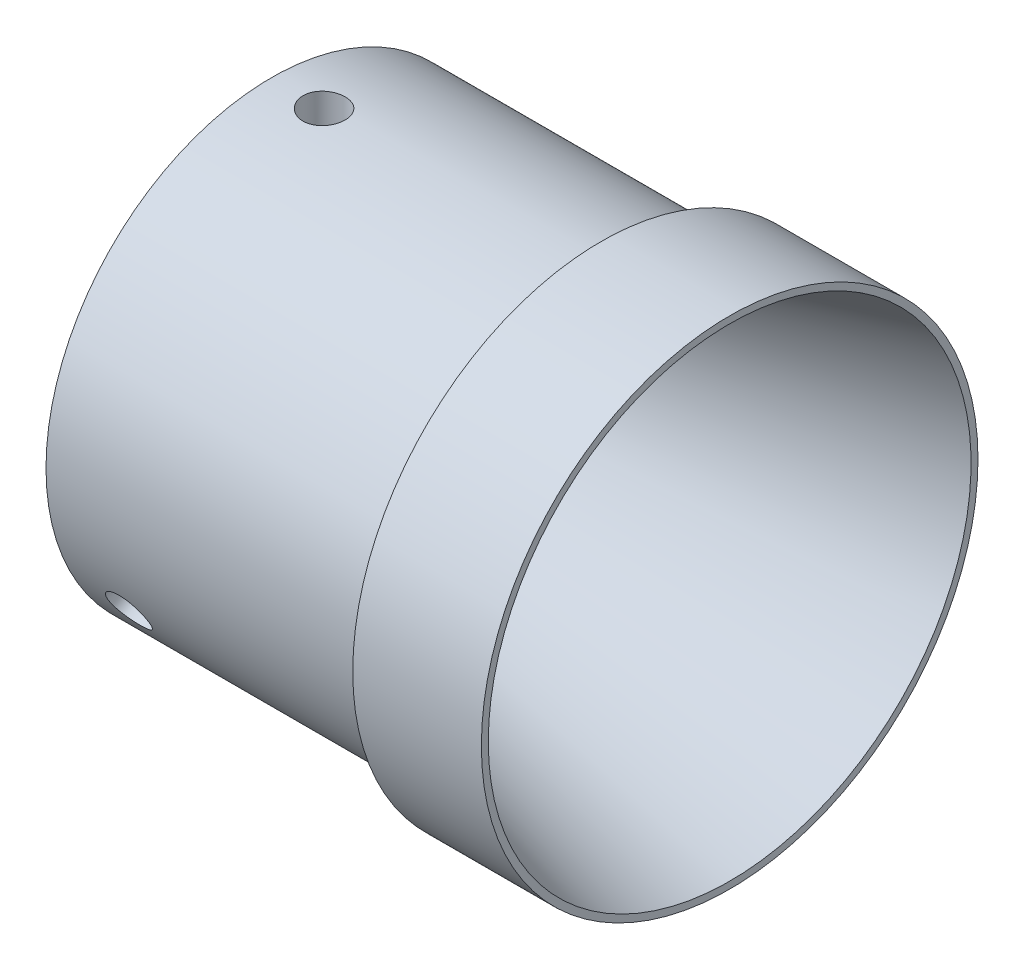
SolidWorks part; units mm, degrees
material "6061-T6 (SS)"
ref_plane "Front Plane" through (0, 0, 0) normal (0, 0, 1) x (1, 0, 0)
ref_plane "Top Plane" through (0, 0, 0) normal (0, 1, 0) x (1, 0, 0)
ref_plane "Right Plane" through (0, 0, 0) normal (1, 0, 0) x (0, 0, -1)
sketch "Sketch1" plane through (0, 0, 0) normal (0, 0, 1) x (1, 0, 0)
  line L0 (0, 14.478) -> (21.1494, 14.478)
  line L1 (21.1494, 14.478) -> (21.1494, 15.9385)
  line L2 (21.1494, 15.9385) -> (29.4044, 15.9385)
  line L3 (29.4044, 15.9385) -> (29.4044, 15.494)
  line L4 (29.4044, 15.494) -> (3.81, 8.636)
  line L5 (3.81, 8.636) -> (3.81, 10.16)
  line L6 (3.81, 10.16) -> (0, 10.16)
  line L7 (0, 10.16) -> (0, 14.478)
  line L8 (0, 0) -> (67.612, 0) construction
  dimension "D1" = 15
  dimension "D2" = 8.255
  dimension "D3" = 14.478
  dimension "D4" = 15.9385
  dimension "D5" = 15.494
  dimension "D6" = 8.636
  dimension "D7" = 3.81
  dimension "D8" = 10.16
revolve "Revolve1" add sketch "Sketch1" angle 360 about L8
ref_plane "Plane1" through (0, 14.478, 0) normal (0, 1, 0) x (1, 0, 0)
hole_wizard "#6-32 Tapped Hole1" positions "Sketch2" profile "Sketch3" tap size "#6-32" standard "ANSI Inch"
sketch "Sketch2" plane through (0, 14.478, 0) normal (0, 1, 0) x (1, 0, 0)
  line L0 (21.1494, 14.478) -> (21.1494, -14.478) construction
  point P0 (3.3694, 0)
  dimension "D1" = 17.78
sketch "Sketch3" plane through (3.3694, 14.478, 0) normal (1, 0, 0) x (0, 0, 1)
  line L0 (0, 0) -> (0, 4.445)
  line L1 (0, 4.445) -> (1.3525, 3.6323)
  line L2 (1.3525, 3.6323) -> (1.3525, 0)
  line L5 (1.3525, 0) -> (0, 0)
  line L10 (0, 4.445) -> (-1.3526, 3.6323) construction
  line L11 (0, -6.35) -> (0, 107.95) construction
  dimension "Tap Drill Dia." = 2.7051
  dimension "Tap Drill Depth" = 4.445
  dimension "Drill Angle" = 118
cosmetic thread "Hole Thread1" parameters "D1"=7.0104, "D2"=3.5052
pattern_circular "CirPattern1" count 3 over 360 about axis through (0, 0, 0) along (-1, 0, 0) of "#6-32 Tapped Hole1"
cosmetic thread "Hole Thread2" parameters "D1"=7.0104, "D2"=3.5052
cosmetic thread "Hole Thread3" parameters "D1"=7.0104, "D2"=3.5052
